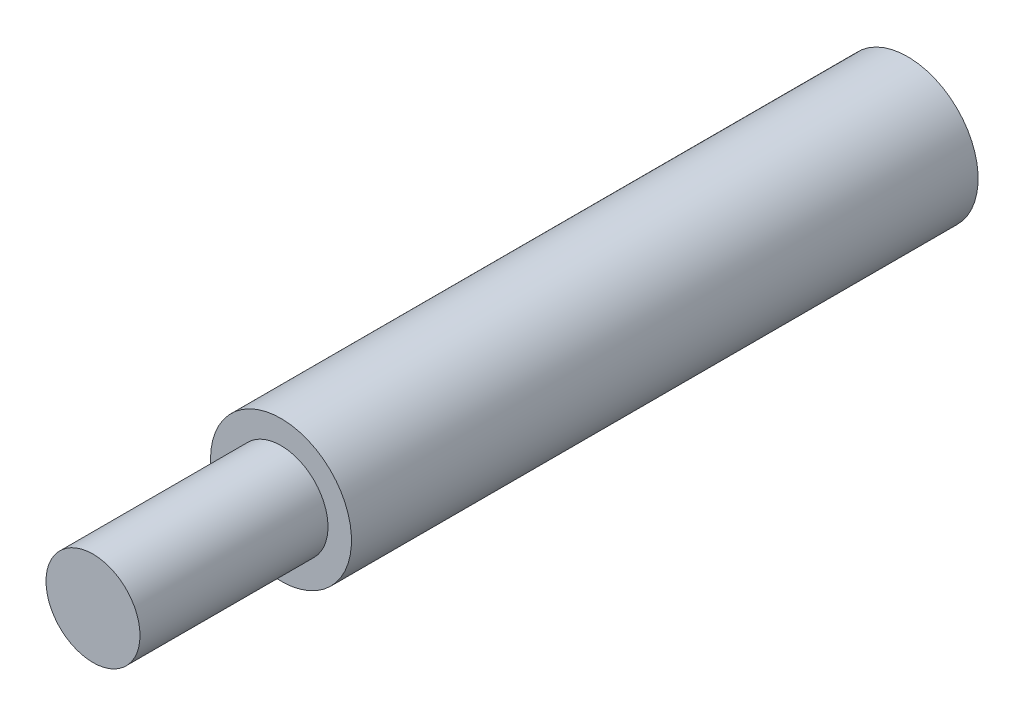
SolidWorks part; units mm, degrees
material "Aluminum"
ref_plane "Front Plane" through (0, 0, 0) normal (0, 0, 1) x (1, 0, 0)
ref_plane "Top Plane" through (0, 0, 0) normal (0, 1, 0) x (1, 0, 0)
ref_plane "Right Plane" through (0, 0, 0) normal (1, 0, 0) x (0, 0, -1)
sketch "Sketch1" plane through (0, 0, 0) normal (0, 0, 1) x (1, 0, 0)
  circle A0 centre (0, 0) radius 1.5
  dimension "D1" = 3
extrude "Boss-Extrude1" add sketch "Sketch1" along normal blind 6
sketch "Sketch2" plane through (0, 0, 0) normal (0, 0, -1) x (-1, 0, 0)
  circle A0 centre (0, 0) radius 2.25
  dimension "D1" = 4.5
extrude "Boss-Extrude2" add sketch "Sketch2" along normal blind 20
sketch "Sketch3" plane through (0, 0, -20) normal (0, 0, -1) x (-1, 0, 0)
  circle A0 centre (0, 0) radius 1.5
  dimension "D1" = 3
extrude "Cut-Extrude1" cut sketch "Sketch3" against normal blind 4.5
